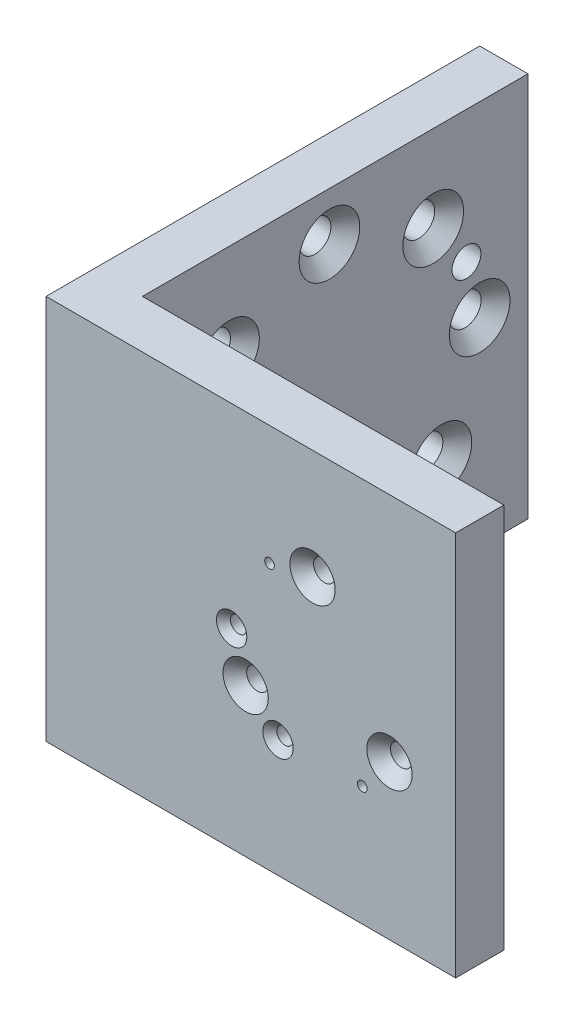
SolidWorks part; units mm, degrees
ref_plane "前基準面" through (0, 0, 0) normal (0, 0, 1) x (1, 0, 0)
ref_plane "上基準面" through (0, 0, 0) normal (0, 1, 0) x (1, 0, 0)
ref_plane "右基準面" through (0, 0, 0) normal (1, 0, 0) x (0, 0, -1)
ref_plane "平面1" through (0, 0, 0) normal (0, -1, 0) x (1, 0, 0)
sketch "草圖1" plane through (0, 0, 0) normal (0, -1, 0) x (1, 0, 0)
  line L0 (0, 0) -> (85, 0)
  line L1 (85, 0) -> (85, 90)
  line L2 (85, 90) -> (0, 90)
  line L3 (0, 90) -> (0, 0)
extrude "填料-伸長1" add sketch "草圖1" against normal blind 80
sketch "草圖2" plane through (0, 80, 0) normal (0, 1, 0) x (-1, 0, 0)
  line L0 (-10, 80) -> (-85, 80)
  line L1 (-85, 80) -> (-85, 0)
  line L2 (-85, 0) -> (-10, 0)
  line L3 (-10, 0) -> (-10, 80)
extrude "除料-伸長1" cut sketch "草圖2" against normal through all
hole_wizard "Ø6.6 (6.6) 直徑孔1" positions "草圖4" profile "草圖3" hole size "Ø6.6" standard "Ansi Metric"
sketch "草圖4" plane through (10, 0, 0) normal (1, 0, 0) x (0, 0, -1)
  point P0 (-38.8076, 10.0237)
  point P1 (-60.3533, 17.9604)
  point P2 (-69.9763, 38.8076)
  point P3 (-62.0396, 60.3533)
  point P4 (-41.1924, 69.9763)
  point P5 (-19.6467, 62.0396)
  point P6 (-10.0237, 41.1924)
  point P7 (-17.9604, 19.6467)
sketch "草圖3" plane through (10, 10.0237, 38.8076) normal (0, 1, 0) x (0, 0, -1)
  line L0 (0, 0) -> (0, 10)
  line L1 (0, 10) -> (3.3, 10)
  line L2 (3.3, 10) -> (3.3, 0)
  line L5 (3.3, 0) -> (0, 0)
  line L11 (0, -6.35) -> (0, 107.95) construction
  dimension "貫穿孔直徑" = 6.6
  dimension "貫穿孔深度" = 10
hole_wizard "Ø6.0 (6) 直徑孔1" positions "草圖6" profile "草圖5" hole size "Ø6.0" standard "Ansi Metric"
sketch "草圖6" plane through (0, 0, 0) normal (-1, 0, 0) x (0, 0, 1)
  point P0 (12.7618, 52.5731)
  point P1 (67.2382, 27.4269)
sketch "草圖5" plane through (0, 52.5731, 12.7618) normal (0, 1, 0) x (0, 0, 1)
  line L0 (0, 0) -> (0, 85)
  line L1 (0, 85) -> (3, 85)
  line L2 (3, 85) -> (3, 0)
  line L5 (3, 0) -> (0, 0)
  line L11 (0, -6.35) -> (0, 107.95) construction
  dimension "貫穿孔直徑" = 6
  dimension "貫穿孔深度" = 85
hole_wizard "Ø2.0 (2) 直徑孔1" positions "草圖8" profile "草圖7" hole size "Ø2.0" standard "Ansi Metric"
sketch "草圖8" plane through (0, 0, 80) normal (0, 0, -1) x (-1, 0, 0)
  point P0 (-46.3774, 55.212)
  point P1 (-65.6226, 24.788)
sketch "草圖7" plane through (46.3774, 55.212, 80) normal (1, 0, 0) x (0, 1, 0)
  line L0 (0, 0) -> (0, 10)
  line L1 (0, 10) -> (1, 10)
  line L2 (1, 10) -> (1, 0)
  line L5 (1, 0) -> (0, 0)
  line L11 (0, -6.35) -> (0, 107.95) construction
  dimension "貫穿孔直徑" = 2
  dimension "貫穿孔深度" = 10
hole_wizard "Ø4.5 (4.5) 直徑孔1" positions "草圖10" profile "草圖9" hole size "Ø4.5" standard "Ansi Metric"
sketch "草圖10" plane through (0, 0, 90) normal (0, 0, 1) x (1, 0, 0)
  point P0 (71.2753, 31.9858)
  point P1 (41.4218, 30.7783)
  point P2 (55.3029, 57.2359)
sketch "草圖9" plane through (71.2753, 31.9858, 90) normal (1, 0, 0) x (0, -1, 0)
  line L0 (0, 0) -> (0, 90)
  line L1 (0, 90) -> (2.25, 90)
  line L2 (2.25, 90) -> (2.25, 0)
  line L5 (2.25, 0) -> (0, 0)
  line L11 (0, -6.35) -> (0, 107.95) construction
  dimension "貫穿孔直徑" = 4.5
  dimension "貫穿孔深度" = 90
hole_wizard "Ø3.4 (3.4) 直徑孔1" positions "草圖12" profile "草圖11" hole size "Ø3.4" standard "Ansi Metric"
sketch "草圖12" plane through (0, 0, 90) normal (0, 0, 1) x (1, 0, 0)
  point P0 (48.1347, 24.3751)
  point P1 (38.512, 39.5871)
sketch "草圖11" plane through (48.1347, 24.3751, 90) normal (1, 0, 0) x (0, -1, 0)
  line L0 (0, 0) -> (0, 90)
  line L1 (0, 90) -> (1.7, 90)
  line L2 (1.7, 90) -> (1.7, 0)
  line L5 (1.7, 0) -> (0, 0)
  line L11 (0, -6.35) -> (0, 107.95) construction
  dimension "貫穿孔直徑" = 3.4
  dimension "貫穿孔深度" = 90
chamfer "導角1" distance 3 angle 45 8 edges at (10, 19.6467, 14.6604) (10, 17.9604, 57.0533) (10, 10.0237, 35.5076) (10, 38.8076, 66.6763) (10, 60.3533, 58.7396) (10, 69.9763, 37.8924) (10, 62.0396, 16.3467) (10, 41.1924, 6.7237)
chamfer "導角2" distance 2.45 angle 45 3 edges at (43.6718, 30.7783, 90) (73.5253, 31.9858, 90) (57.5529, 57.2359, 90)
chamfer "導角3" distance 1.45 angle 45 2 edges at (40.212, 39.5871, 90) (49.8347, 24.3751, 90)
